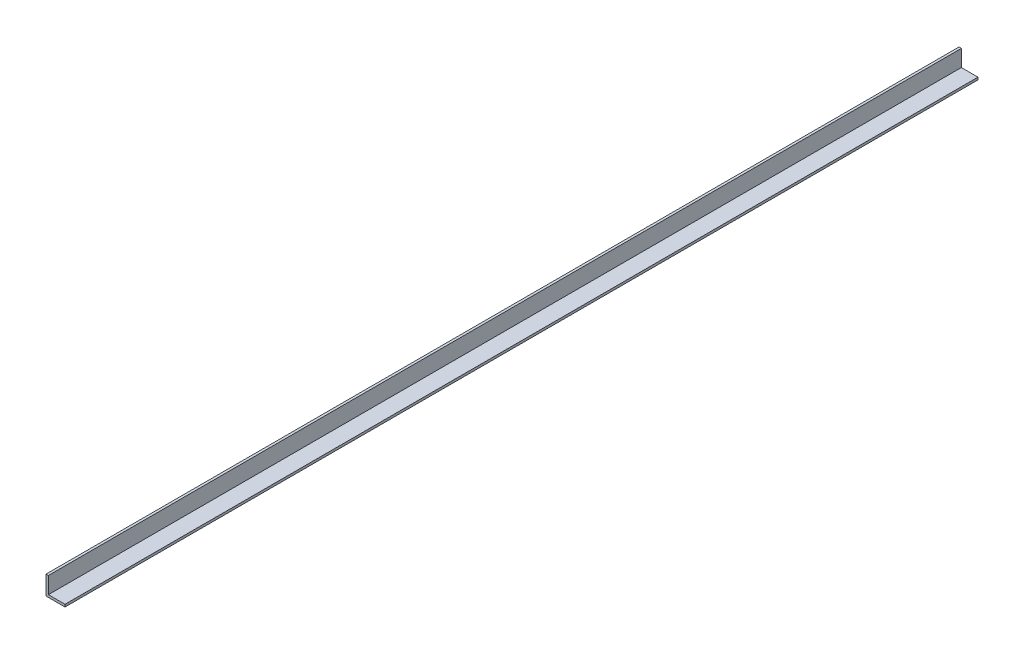
SolidWorks part; units mm, degrees
ref_plane "Front Plane" through (0, 0, 0) normal (0, 0, 1) x (1, 0, 0)
ref_plane "Top Plane" through (0, 0, 0) normal (0, 1, 0) x (1, 0, 0)
ref_plane "Right Plane" through (0, 0, 0) normal (1, 0, 0) x (0, 0, -1)
sketch "Sketch1" plane through (0, 0, 0) normal (0, 0, 1) x (1, 0, 0)
  line L1 (0, 0) -> (1.6002, 0)
  line L2 (0, 0) -> (0, 12.7)
  line L3 (0, 12.7) -> (1.6002, 12.7)
  line L4 (1.6002, 1.6002) -> (1.6002, 12.7)
  line L5 (0, 0) -> (12.7, 0)
  line L6 (0, 0) -> (0, 1.6002)
  line L7 (1.6002, 1.6002) -> (12.7, 1.6002)
  line L8 (12.7, 0) -> (12.7, 1.6002)
  dimension "D1" = 12.7
  dimension "D2" = 12.7
  dimension "D3" = 1.6002
  dimension "D4" = 1.6002
extrude "Boss-Extrude1" add sketch "Sketch1" along normal blind 609.6 contours L5 L8 L7 L4 L3 L2 L1
